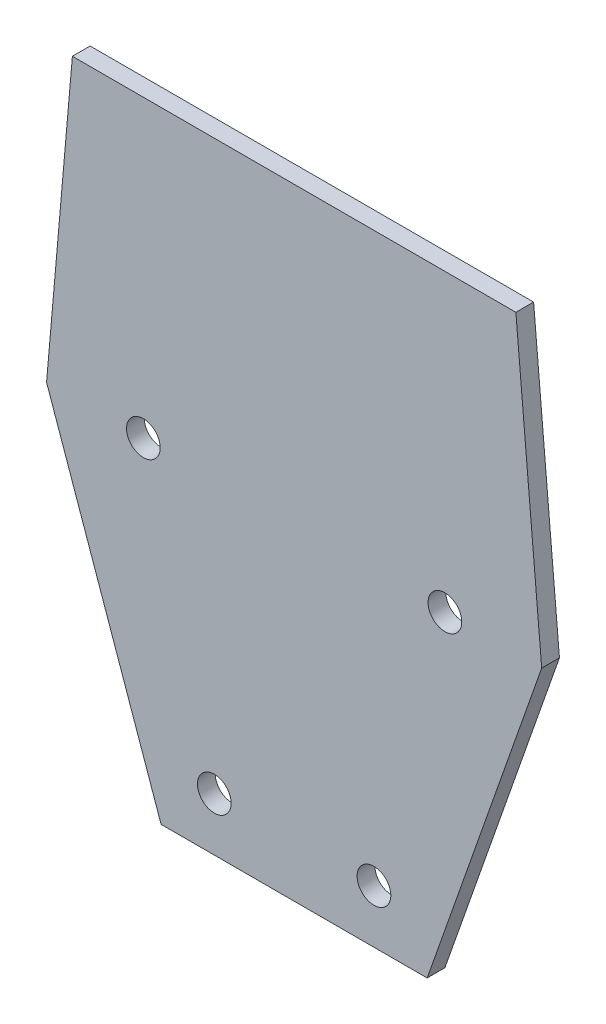
SolidWorks part; units mm, degrees
ref_plane "Front Plane" through (0, 0, 0) normal (0, 0, 1) x (1, 0, 0)
ref_plane "Top Plane" through (0, 0, 0) normal (0, 1, 0) x (1, 0, 0)
ref_plane "Right Plane" through (0, 0, 0) normal (1, 0, 0) x (0, 0, -1)
sketch "Sketch1" plane through (0, 0, 0) normal (0, 0, 1) x (1, 0, 0)
  line L0 (-31.75, 28.792) -> (31.75, 28.792)
  line L1 (31.75, 28.792) -> (35.4483, -13.4796)
  line L2 (35.4483, -13.4796) -> (19.05, -60.108)
  line L3 (19.05, -60.108) -> (-19.05, -60.108)
  line L4 (-31.75, 28.792) -> (-35.4483, -13.4796)
  line L5 (-35.4483, -13.4796) -> (-19.05, -60.108)
  point P2 (0, 28.792)
  point P6 (0, -60.108)
  dimension "D1" = 0
  dimension "D2" = 63.5
  dimension "D3" = 0
  dimension "D4" = 38.1
  dimension "D5" = 95
  dimension "D6" = 95
  dimension "D7" = 0
  dimension "D8" = 88.9
extrude "Boss-Extrude1" add sketch "Sketch1" along normal blind 2.54 contours L0 L1 L2 L3 L5 L4
sketch "Sketch3" plane through (0, 0, 0) normal (0, 0, -1) x (-1, 0, 0)
  line L0 (-19.05, -60.108) -> (19.05, -60.108) construction
  circle A0 centre (11.43, -52.488) radius 2.413
  circle A1 centre (-11.43, -52.488) radius 2.413
  circle A2 centre (21.59, -13.4796) radius 2.413
  circle A3 centre (-21.59, -13.4796) radius 2.413
  point P13 (0, 0)
  point P14 (0, 0)
  dimension "D1" = 7.62
  dimension "D3" = 4.826
  dimension "D6" = 4.826
  dimension "D7" = 0
  dimension "D2" = 7.62
  dimension "D4" = 7.62
  dimension "D5" = 7.62
  dimension "D8" = 0
  dimension "D9" = 2.54
  dimension "D10" = 2.54
extrude "Cut-Extrude1" cut sketch "Sketch3" against normal through all
